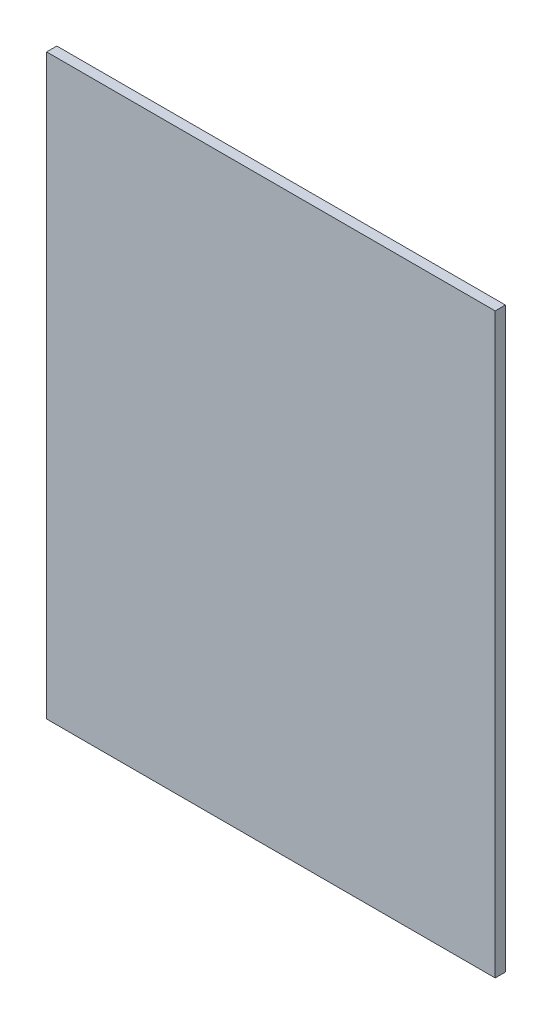
SolidWorks part; units mm, degrees
material "Glass"
ref_plane "Front Plane" through (0, 0, 0) normal (0, 0, 1) x (1, 0, 0)
ref_plane "Top Plane" through (0, 0, 0) normal (0, 1, 0) x (1, 0, 0)
ref_plane "Right Plane" through (0, 0, 0) normal (1, 0, 0) x (0, 0, -1)
sketch "Sketch1" plane through (0, 0, 0) normal (0, 0, 1) x (1, 0, 0)
  line L1 (-35.8278, 1016.8657) -> (802.3722, 1016.8657)
  line L2 (-35.8278, 1016.8657) -> (-35.8278, -62.6343)
  line L3 (-35.8278, -62.6343) -> (802.3722, -62.6343)
  line L4 (802.3722, 1016.8657) -> (802.3722, -62.6343)
extrude "Boss-Extrude1" add sketch "Sketch1" along normal blind 19.05 contours L2 L1 L4 L3
